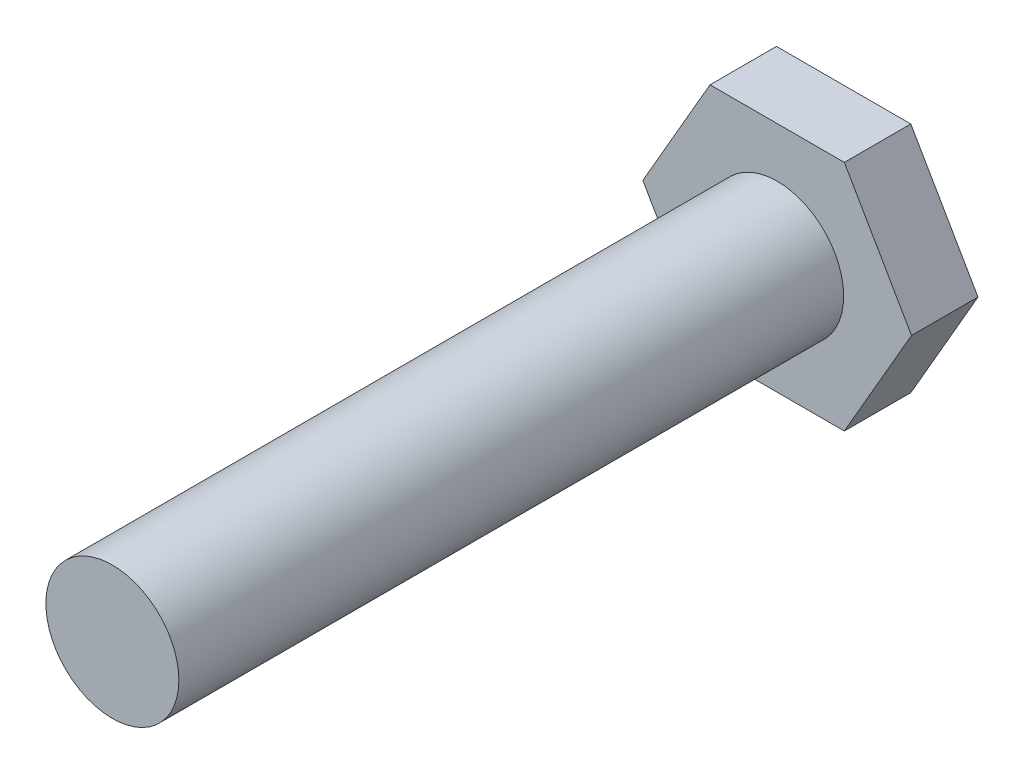
SolidWorks part; units mm, degrees
ref_plane "Front Plane" through (0, 0, 0) normal (0, 0, 1) x (1, 0, 0)
ref_plane "Top Plane" through (0, 0, 0) normal (0, 1, 0) x (1, 0, 0)
ref_plane "Right Plane" through (0, 0, 0) normal (1, 0, 0) x (0, 0, -1)
sketch "Sketch1" plane through (0, 0, 0) normal (0, 0, 1) x (1, 0, 0)
  circle A0 centre (0, 0) radius 10
  dimension "D1" = 20
extrude "Boss-Extrude1" add sketch "Sketch1" along normal blind 100
cosmetic thread "Cosmetic Thread1"
sketch "Sketch3" plane through (0, 0, 0) normal (0, 0, -1) x (-1, 0, 0)
  line L1 (20.2073, 0) -> (10.1036, 17.5)
  line L2 (10.1036, 17.5) -> (-10.1036, 17.5)
  line L3 (-10.1036, 17.5) -> (-20.2073, 0)
  line L4 (-20.2073, 0) -> (-10.1036, -17.5)
  line L5 (-10.1036, -17.5) -> (10.1036, -17.5)
  line L6 (10.1036, -17.5) -> (20.2073, 0)
  circle A0 centre (0, 0) radius 17.5 construction
  dimension "D1" = 35
extrude "Boss-Extrude2" add sketch "Sketch3" along normal blind 10
